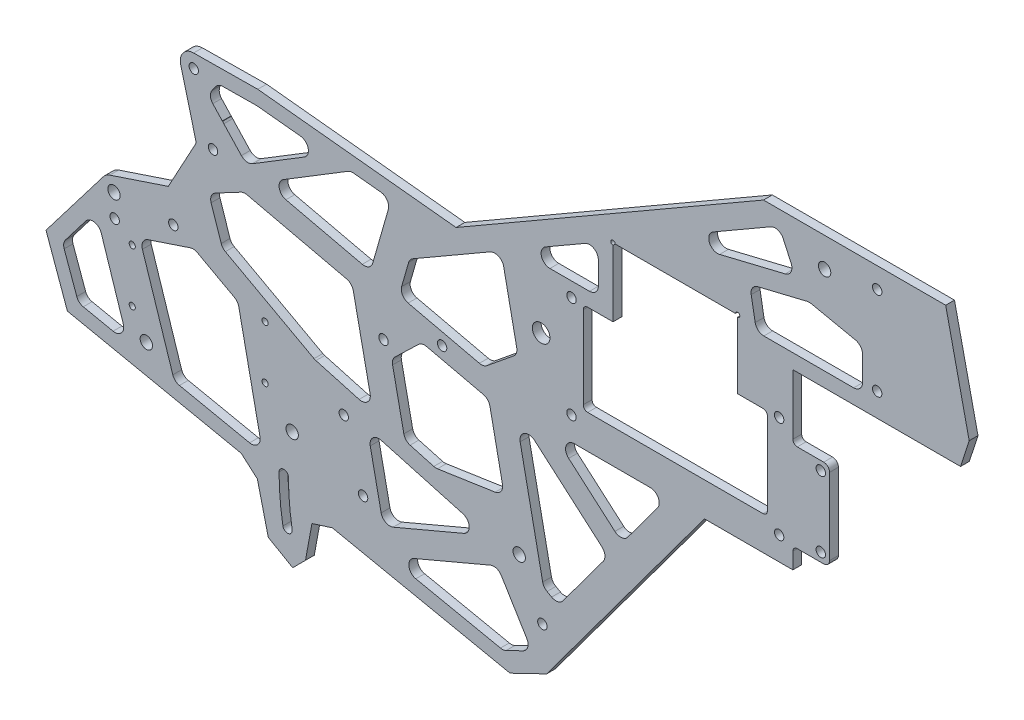
SolidWorks part; units mm, degrees
material "Thornel Mat VMA"
ref_plane "Front Plane" through (0, 0, 0) normal (0, 0, 1) x (1, 0, 0)
ref_plane "Top Plane" through (0, 0, 0) normal (0, 1, 0) x (1, 0, 0)
ref_plane "Right Plane" through (0, 0, 0) normal (1, 0, 0) x (0, 0, -1)
sketch "Sketch1" plane through (0, 0, 0) normal (0, 0, 1) x (1, 0, 0)
  line L1 (-20.4587, 47.6) -> (-183.6375, 47.6)
  line L2 (-20.4587, 47.6) -> (-20.4587, -36.0143)
  line L3 (-20.4587, -36.0143) -> (-183.6375, -36.0143)
  line L4 (-183.6375, 47.6) -> (-183.6375, -36.0143)
extrude "Boss-Extrude1" add sketch "Sketch1" along normal blind 3
sketch "Sketch2" plane through (0, 0, 3) normal (0, 0, 1) x (1, 0, 0)
  circle A0 centre (-24.2887, 24) radius 3
  dimension "D1" = 6
extrude "Cut-Extrude1" cut sketch "Sketch2" against normal blind 70
sketch "Sketch3" plane through (0, 0, 3) normal (0, 0, 1) x (1, 0, 0)
  line L4 (-20.4587, -36.0143) -> (-20.4587, 47.6)
  line L5 (-20.4587, 47.6) -> (-183.6375, 47.6)
  line L6 (-183.6375, 47.6) -> (-183.6375, -36.0143)
  line L7 (-183.6375, -36.0143) -> (-20.4587, -36.0143)
  line L8 (-20.4587, -36.0143) -> (-20.4587, 47.6)
  line L9 (-20.4587, 47.6) -> (-41.1202, 47.6)
  line L10 (-183.6375, 47.6) -> (-183.6375, -36.0143)
  line L11 (-183.6375, -36.0143) -> (-20.4587, -36.0143)
  line L13 (51.3713, 101) -> (-41.1202, 47.6)
  line L14 (-41.1202, 47.6) -> (-120.7247, 47.6)
  line L15 (-204.873, 47.6) -> (-204.873, -81.5667)
  line L16 (-204.873, -81.5667) -> (-34.873, -81.5667)
  line L17 (-34.873, -81.5667) -> (61.3713, -26)
  line L18 (61.3713, -26) -> (61.3713, 2.5)
  line L19 (62.8713, 4) -> (71.8713, 4)
  line L20 (73.8713, 6) -> (73.8713, 32)
  line L21 (71.8713, 34) -> (62.8713, 34)
  line L22 (61.3713, 35.5) -> (61.3713, 56)
  line L23 (61.3713, 56) -> (121.3713, 56)
  line L24 (121.3713, 56) -> (121.3713, 101)
  line L25 (121.3713, 101) -> (51.3713, 101)
  line L26 (51.3713, 101) -> (-41.1202, 47.6)
  line L27 (-167.8527, 47.6) -> (-120.7247, 47.6)
  line L28 (-204.873, 47.6) -> (-204.873, -81.5667)
  line L29 (-204.873, -81.5667) -> (-34.873, -81.5667)
  line L30 (-34.873, -81.5667) -> (61.3713, -26)
  line L31 (61.3713, -26) -> (61.3713, 2.5)
  line L32 (62.8713, 4) -> (71.8713, 4)
  line L33 (73.8713, 6) -> (73.8713, 32)
  line L34 (71.8713, 34) -> (62.8713, 34)
  line L35 (61.3713, 35.5) -> (61.3713, 56)
  line L36 (61.3713, 56) -> (121.3713, 56)
  line L37 (121.3713, 56) -> (121.3713, 101)
  line L38 (121.3713, 101) -> (51.3713, 101)
  line L265 (-167.8527, 47.6) -> (-204.873, 47.6)
  line L266 (-183.6375, 47.6) -> (-204.873, 47.6)
  circle A0 centre (70.8713, 31) radius 1.6 construction
  circle A1 centre (70.8713, 7) radius 1.6 construction
  arc A2 (71.8713, 4) -> (73.8713, 6) centre (71.8713, 6) ccw
  arc A3 (73.8713, 32) -> (71.8713, 34) centre (71.8713, 32) ccw
  arc A4 (71.8713, 4) -> (73.8713, 6) centre (71.8713, 6) ccw
  arc A5 (73.8713, 32) -> (71.8713, 34) centre (71.8713, 32) ccw
  circle A6 centre (70.8713, 31) radius 1.6
  circle A7 centre (70.8713, 7) radius 1.6
  arc A38 (62.8713, 4) -> (61.3713, 2.5) centre (62.8713, 2.5) ccw
  arc A39 (62.8713, 4) -> (61.3713, 2.5) centre (62.8713, 2.5) ccw
  arc A40 (61.3713, 35.5) -> (62.8713, 34) centre (62.8713, 35.5) ccw
  arc A41 (61.3713, 35.5) -> (62.8713, 34) centre (62.8713, 35.5) ccw
  arc A60 (-120.7247, 47.6) -> (-167.8527, 47.6) centre (-144.2887, 24) ccw
  arc A61 (-120.7247, 47.6) -> (-167.8527, 47.6) centre (-144.2887, 24) ccw
  dimension "D1" = 0
  dimension "D2" = 0
extrude "Boss-Extrude2" add sketch "Sketch3" against normal blind 3
sketch "Sketch4" plane through (0, 0, 3) normal (0, 0, 1) x (1, 0, 0)
  line L0 (0.1713, 62.05) -> (0.1713, 39.5) construction
  line L2 (-9.9587, 10) -> (-9.9587, 38) construction
  line L3 (-8.4587, 8.5) -> (51.2013, 8.5) construction
  line L4 (52.7013, 10) -> (52.7013, 38) construction
  line L7 (41.8213, 62.8) -> (0.9213, 62.8) construction
  line L8 (0.1713, 62.05) -> (0.1713, 39.5)
  line L9 (-8.4587, 39.5) -> (0.1713, 39.5)
  line L10 (-9.9587, 10) -> (-9.9587, 38)
  line L11 (-8.4587, 8.5) -> (51.2013, 8.5)
  line L12 (52.7013, 10) -> (52.7013, 38)
  line L13 (42.5713, 39.5) -> (51.2013, 39.5)
  line L14 (42.5713, 62.05) -> (42.5713, 39.5)
  line L15 (41.8213, 62.8) -> (0.9213, 62.8)
  arc A1 (-8.4587, 39.5) -> (-9.9587, 38) centre (-8.4587, 38) ccw construction
  arc A2 (-9.9587, 10) -> (-8.4587, 8.5) centre (-8.4587, 10) ccw construction
  arc A3 (51.2013, 8.5) -> (52.7013, 10) centre (51.2013, 10) ccw construction
  arc A4 (52.7013, 38) -> (51.2013, 39.5) centre (51.2013, 38) ccw construction
  arc A5 (42.5713, 62.05) -> (41.8213, 62.8) centre (42.5713, 62.8) ccw construction
  arc A6 (0.9213, 62.8) -> (0.1713, 62.05) centre (0.1713, 62.8) ccw
  arc A7 (-8.4587, 39.5) -> (-9.9587, 38) centre (-8.4587, 38) ccw
  arc A8 (-9.9587, 10) -> (-8.4587, 8.5) centre (-8.4587, 10) ccw
  arc A9 (51.2013, 8.5) -> (52.7013, 10) centre (51.2013, 10) ccw
  arc A10 (52.7013, 38) -> (51.2013, 39.5) centre (51.2013, 38) ccw
  arc A11 (42.5713, 62.05) -> (41.8213, 62.8) centre (42.5713, 62.8) ccw
extrude "Cut-Extrude2" cut sketch "Sketch4" against normal blind 10
sketch "Sketch6" plane through (0, 0, 0) normal (0, 0, -1) x (-1, 0, 0)
  line L0 (-121.3713, 101) -> (-51.3713, 101) construction
  line L1 (-121.3713, 56) -> (-121.3713, 101) construction
  line L2 (204.873, -81.5667) -> (34.873, -81.5667) construction
  line L3 (-61.3713, -26) -> (-61.3713, 2.5) construction
  line L4 (204.873, 47.6) -> (204.873, -81.5667) construction
  circle A2 centre (158.6381, -45.9257) radius 2.1
  circle A3 centre (169.6384, -7.2338) radius 2.1
  circle A4 centre (109.0119, -47.5134) radius 2.1
  circle A5 centre (31.7556, -45.033) radius 2.1
  circle A6 centre (-71.9717, 91) radius 2.1
  dimension "D1" = 10
  dimension "D2" = 49.3996
  dimension "D3" = 36.5337
  dimension "D4" = 93.1269
  dimension "D5" = 34.0533
  dimension "D6" = 95.8611
  dimension "D7" = 35.641
  dimension "D8" = 46.2349
  dimension "D9" = 35.2346
  dimension "D10" = 74.3329
  dimension "D11" = 4.2
extrude "Cut-Extrude3" cut sketch "Sketch6" against normal blind 10
sketch "Sketch7" plane through (0, 0, 3) normal (0, 0, 1) x (1, 0, 0)
  circle A0 centre (56.7013, 5) radius 1.6
  circle A1 centre (-13.9587, 5) radius 1.6
  circle A2 centre (56.7013, 39.6) radius 1.6
  circle A3 centre (-13.9587, 39.6) radius 1.6
  dimension "D1" = 3.2
extrude "Cut-Extrude4" cut sketch "Sketch7" against normal blind 10
sketch "Sketch8" plane through (0, 0, 0) normal (0, 0, -1) x (-1, 0, 0)
  circle A0 centre (163.4287, -37.6667) radius 1.05
  circle A1 centre (163.4287, -19.6667) radius 1.05
  circle A2 centre (118.2287, -37.6667) radius 1.05
  circle A3 centre (118.2287, -19.6667) radius 1.05
  dimension "D1" = 2.1
extrude "Cut-Extrude5" cut sketch "Sketch8" against normal blind 10
sketch "Sketch9" plane through (0, 0, 0) normal (0, 0, -1) x (-1, 0, 0)
  line L0 (-118.4267, 56) -> (-121.3713, 65.0628)
  line L1 (-61.3713, 56) -> (-121.3713, 56) construction
  line L2 (-121.3713, 65.0628) -> (-121.3713, 56)
  line L3 (-121.3713, 56) -> (-118.4267, 56)
  line L4 (-121.3713, 65.0628) -> (-113.3713, 101)
  line L5 (-113.3713, 101) -> (-121.3713, 101)
  line L6 (-121.3713, 101) -> (-121.3713, 65.0628)
  line L7 (-17.2669, -51.4637) -> (-61.3713, 0.5)
  line L8 (34.873, -81.5667) -> (-61.3713, -26) construction
  line L9 (-61.3713, 0.5) -> (-61.3713, -26)
  line L10 (-61.3713, -26) -> (-17.2669, -51.4637)
  line L11 (104.2003, -81.5667) -> (102.2857, -71.1635)
  line L12 (102.2857, -71.1635) -> (95.3446, -68.9652)
  line L13 (95.3446, -68.9652) -> (34.873, -81.5667)
  line L14 (34.873, -81.5667) -> (104.2003, -81.5667)
  line L15 (117.4045, -81.5667) -> (120.8632, -67.2922)
  line L16 (204.873, -81.5667) -> (34.873, -81.5667) construction
  line L17 (120.8632, -67.2922) -> (126.3485, -62.5044)
  line L18 (126.3485, -62.5044) -> (185.4974, -50.1785)
  line L19 (185.4974, -50.1785) -> (192.7819, -29.967)
  line L20 (192.7819, -29.967) -> (177.6384, -10.1551)
  line L21 (177.6384, -10.1551) -> (177.6384, 23.9998)
  line L22 (177.6384, 23.9998) -> (204.873, 23.9998)
  line L23 (204.873, 47.6) -> (204.873, -81.5667) construction
  line L24 (204.873, 23.9998) -> (204.873, -81.5667)
  line L25 (204.873, -81.5667) -> (117.4045, -81.5667)
  line L26 (-50.2448, 61) -> (-83.5713, 61)
  line L28 (-85.0713, 62.5) -> (-85.0713, 73.769)
  line L30 (-83.9897, 75.2094) -> (-66.2924, 80.35)
  line L32 (-65.5204, 80.3673) -> (-47.7224, 76.05)
  line L34 (-46.5996, 74.3275) -> (-48.7684, 62.2352)
  line L36 (-25.3142, 76.7885) -> (-59.5197, 85.0857)
  line L38 (-60.5306, 87.1663) -> (-56.3939, 96.2292)
  line L40 (-54.2793, 96.9054) -> (-24.2105, 79.5452)
  line L41 (9.9587, 10) -> (9.9587, 38) construction
  line L42 (-51.2013, 8.5) -> (8.4587, 8.5) construction
  arc A0 (-48.7684, 62.2352) -> (-50.2448, 61) centre (-50.2448, 62.5) cw
  arc A1 (-46.5996, 74.3275) -> (-47.7224, 76.05) centre (-48.076, 74.5923) ccw
  arc A2 (-83.5713, 61) -> (-85.0713, 62.5) centre (-83.5713, 62.5) cw
  arc A3 (-85.0713, 73.769) -> (-83.9897, 75.2094) centre (-83.5713, 73.769) cw
  arc A4 (-65.5204, 80.3673) -> (-66.2924, 80.35) centre (-65.874, 78.9096) ccw
  arc A5 (-25.3142, 76.7885) -> (-24.2105, 79.5452) centre (-24.9605, 78.2462) ccw
  arc A6 (-59.5197, 85.0857) -> (-60.5306, 87.1663) centre (-59.1661, 86.5434) cw
  arc A7 (-54.2793, 96.9054) -> (-56.3939, 96.2292) centre (-55.0293, 95.6064) ccw
  line M29 (204.873, -81.5667) -> (204.873, 47.6)
  line M34 (-51.3713, 101) -> (-121.3713, 101)
  line M35 (-121.3713, 101) -> (-121.3713, 56)
  line M36 (-121.3713, 56) -> (-61.3713, 56)
  line M45 (-61.3713, 2.5) -> (-61.3713, -26)
  line M46 (-61.3713, -26) -> (34.873, -81.5667)
  line M47 (34.873, -81.5667) -> (204.873, -81.5667)
  dimension "D1" = 1.5
  dimension "D2" = 85.3859
  dimension "D3" = 92.327
  dimension "D4" = 94.2416
  dimension "D5" = 107.4459
  dimension "D6" = 110.9045
  dimension "D7" = 116.3898
  dimension "D8" = 167.6797
  dimension "D9" = 34.1692
  dimension "D10" = 175.5387
  dimension "D11" = 182.8232
  dimension "D12" = 27.2256
  dimension "D13" = 34.9192
  dimension "D14" = 35.2728
  dimension "D15" = 56.5583
  dimension "D16" = 57.6811
  dimension "D17" = 58.0347
  dimension "D18" = 58.7271
  dimension "D19" = 64.238
  dimension "D20" = 66.3526
  dimension "D21" = 75.4791
  dimension "D22" = 76.2511
  dimension "D23" = 93.9484
  dimension "D24" = 15.4998
  dimension "D25" = 52.5
  dimension "D26" = 68.2885
  dimension "D27" = 56.5628
  dimension "D28" = 58.6785
  dimension "D29" = 75.7922
  dimension "D32" = 123.33
  dimension "D33" = 128.3853
  dimension "D47" = 8
  dimension "D48" = 18.6551
  dimension "D49" = 38.467
extrude "Cut-Extrude6" cut sketch "Sketch9" against normal blind 10 contours L22 L21 L20 L19 L18 L17 L15 M47 M29 | L12 L13 L11 M47 | L7 M46 M45 | L32 A4 L30 A3 L28 A2 L26 A0 L34 A1 | L40 A7 L38 A6 L36 A5 | L0 M36 M35 | L4 M35 M34
sketch "Sketch10" plane through (0, 0, 3) normal (0, 0, 1) x (1, 0, 0)
  line L0 (17.2669, -51.4637) -> (10.2058, -59.7831)
  line L1 (10.2058, -59.7831) -> (-34.873, -81.5667)
  line L2 (-34.873, -81.5667) -> (17.2669, -51.4637)
  line L3 (-9.9587, 38) -> (-9.9587, 10) construction
  line L4 (-8.4587, 8.5) -> (51.2013, 8.5) construction
  dimension "D1" = 20.1645
  dimension "D2" = 68.2831
extrude "Boss-Extrude3" add sketch "Sketch10" against normal blind 3
sketch "Sketch11" plane through (0, 0, 0) normal (0, 0, -1) x (-1, 0, 0)
  line L0 (182.0256, -45.065) -> (186.8761, -31.6065)
  line L1 (204.873, 47.6) -> (204.873, 23.9998) construction
  line L2 (186.6567, -30.187) -> (177.4937, -18.1993)
  line L3 (-113.3713, 101) -> (-51.3713, 101) construction
  line L4 (174.8756, -18.6461) -> (165.68, -46.9072)
  line L6 (167.4124, -48.8398) -> (180.9204, -46.0249)
  arc A0 (112.1618, -76.8394) -> (109.0086, -76.294) centre (110.5852, -76.5667) cw
  arc A1 (112.1618, -76.8394) -> (113.473, -61.5667) centre (23.873, -61.5667) ccw
  arc A2 (110.273, -61.5667) -> (109.0086, -76.294) centre (23.873, -61.5667) cw
  arc A3 (113.473, -61.5667) -> (110.273, -61.5667) centre (111.873, -61.5667) ccw
  circle A4 centre (23.873, -61.5667) radius 1.6
  arc A5 (180.9204, -46.0249) -> (182.0256, -45.065) centre (180.6144, -44.5564) ccw
  arc A6 (186.8761, -31.6065) -> (186.6567, -30.187) centre (185.465, -31.0979) ccw
  arc A7 (177.4937, -18.1993) -> (174.8756, -18.6461) centre (176.302, -19.1102) ccw
  arc A8 (167.4124, -48.8398) -> (165.68, -46.9072) centre (167.1064, -47.3713) cw
  dimension "D1" = 1.6
  dimension "D2" = 89.6
  dimension "D3" = 17.9969
  dimension "D4" = 1.5
  dimension "D5" = 18.2163
  dimension "D6" = 19.408
  dimension "D7" = 22.8475
  dimension "D8" = 23.9526
  dimension "D9" = 27.3793
  dimension "D10" = 29.9974
  dimension "D11" = 92.7112
  dimension "D12" = 93
  dimension "D13" = 119.1993
  dimension "D14" = 162.5667
extrude "Cut-Extrude7" cut sketch "Sketch11" against normal blind 3
sketch "Sketch12" plane through (0, 0, 0) normal (0, 0, -1) x (-1, 0, 0)
  line L0 (204.873, 47.6) -> (204.873, 23.9998) construction
  line L1 (-113.3713, 101) -> (-51.3713, 101) construction
  circle A0 centre (-90.0713, 94) radius 1.6
  circle A1 centre (-90.0713, 64) radius 1.6
  dimension "D1" = 3.2
  dimension "D2" = 294.9443
  dimension "D3" = 7
  dimension "D4" = 37
extrude "Cut-Extrude8" cut sketch "Sketch12" against normal blind 3
sketch "Sketch15" plane through (0, 0, 3) normal (0, 0, 1) x (1, 0, 0)
  line L0 (-104.2003, -81.5667) -> (-117.4045, -81.5667)
  line L1 (-117.4045, -81.5667) -> (-117.1382, -82.6658)
  line L2 (-117.1382, -82.6658) -> (-108.8293, -87.4629)
  line L3 (-108.8293, -87.4629) -> (-104.4861, -83.1198)
  line L4 (-104.4861, -83.1198) -> (-104.2003, -81.5667)
  line L5 (52.7013, 10) -> (52.7013, 38) construction
  line L6 (41.8213, 62.8) -> (0.9213, 62.8) construction
  dimension "D1" = 157.1875
  dimension "D2" = 161.5306
  dimension "D3" = 169.8396
  dimension "D4" = 145.4658
  dimension "D5" = 145.9198
  dimension "D6" = 150.2629
extrude "Boss-Extrude4" add sketch "Sketch15" against normal blind 3
sketch "Sketch16" plane through (0, 0, 0) normal (0, 0, -1) x (-1, 0, 0)
  line L0 (11.2698, -56.8332) -> (-11.3083, -45.9227)
  line L1 (0.4601, -6.3291) -> (-30.5111, -21.7344)
  line L2 (-11.7993, -45.5427) -> (-23.6576, -31.5713)
  line L3 (204.873, 47.6) -> (204.873, 23.9998) construction
  line L4 (-23.182, -29.2577) -> (27.4491, -4.0733)
  line L5 (-32.3227, -21.3621) -> (-41.0149, -11.1209)
  line L6 (29.5868, -5.7168) -> (22.3602, -41.0637)
  line L7 (-61.3713, 56) -> (-118.4267, 56) construction
  line L8 (22.1716, -41.5438) -> (13.2034, -56.2631)
  line L9 (-41.3713, -10.1503) -> (-41.3713, -1)
  line L11 (-39.8713, 0.5) -> (-2.7749, 0.5)
  line L13 (-1.5138, -0.1879) -> (1.0532, -4.174)
  arc A0 (13.2034, -56.2631) -> (11.2698, -56.8332) centre (11.9225, -55.4826) cw
  arc A1 (22.1716, -41.5438) -> (22.3602, -41.0637) centre (20.8906, -40.7633) ccw
  arc A2 (29.5868, -5.7168) -> (27.4491, -4.0733) centre (28.1172, -5.4164) ccw
  arc A3 (-11.3083, -45.9227) -> (-11.7993, -45.5427) centre (-10.6557, -44.5721) cw
  arc A4 (-23.6576, -31.5713) -> (-23.182, -29.2577) centre (-22.514, -30.6007) cw
  arc A5 (0.4601, -6.3291) -> (1.0532, -4.174) centre (-0.208, -4.9861) ccw
  arc A6 (-1.5138, -0.1879) -> (-2.7749, 0.5) centre (-2.7749, -1) ccw
  arc A7 (-30.5111, -21.7344) -> (-32.3227, -21.3621) centre (-31.1791, -20.3914) cw
  arc A8 (-41.0149, -11.1209) -> (-41.3713, -10.1503) centre (-39.8713, -10.1503) cw
  arc A9 (-41.3713, -1) -> (-39.8713, 0.5) centre (-39.8713, -1) cw
  dimension "D1" = 1.5
  dimension "D2" = 175.2862
  dimension "D3" = 176.7558
  dimension "D4" = 177.4239
  dimension "D5" = 182.5128
  dimension "D6" = 182.7014
  dimension "D7" = 191.6696
  dimension "D8" = 193.6032
  dimension "D9" = 203.8199
  dimension "D10" = 204.413
  dimension "D11" = 205.081
  dimension "D12" = 206.3868
  dimension "D13" = 215.5287
  dimension "D14" = 216.6723
  dimension "D15" = 235.3841
  dimension "D16" = 245.888
  dimension "D17" = 55.5
extrude "Cut-Extrude11" cut sketch "Sketch16" against normal blind 3
sketch "Sketch18" plane through (0, 0, 0) normal (0, 0, -1) x (-1, 0, 0)
  line L0 (7.0787, 61.4804) -> (31.6415, 47.299)
  line L1 (-52.7013, 38) -> (-52.7013, 10) construction
  line L2 (30.8915, 44.5) -> (6.3287, 44.5)
  line L3 (-0.9213, 62.8) -> (-41.8213, 62.8) construction
  line L4 (4.8287, 46) -> (4.8287, 60.1813)
  arc A0 (4.8287, 60.1813) -> (7.0787, 61.4804) centre (6.3287, 60.1813) cw
  arc A1 (4.8287, 46) -> (6.3287, 44.5) centre (6.3287, 46) ccw
  arc A2 (31.6415, 47.299) -> (30.8915, 44.5) centre (30.8915, 46) cw
  dimension "D1" = 1.5
  dimension "D2" = 57.53
  dimension "D3" = 59.78
  dimension "D4" = 83.5928
  dimension "D5" = 1.3196
extrude "Cut-Extrude13" cut sketch "Sketch18" against normal blind 3
sketch "Sketch19" plane through (0, 0, 3) normal (0, 0, 1) x (1, 0, 0)
  line L0 (52.7013, 10) -> (52.7013, 38) construction
  line L1 (41.8213, 62.8) -> (0.9213, 62.8) construction
  circle A0 centre (-91.4566, -33.7689) radius 1.6
  circle A1 centre (-77.9328, -4.7671) radius 1.6
  circle A2 centre (-149.4603, -6.7213) radius 1.6
  circle A3 centre (-135.9365, 22.2805) radius 1.6
  dimension "D1" = 3.2
  dimension "D2" = 130.6341
  dimension "D3" = 144.1579
  dimension "D4" = 188.6378
  dimension "D5" = 202.1616
  dimension "D6" = 40.5195
  dimension "D7" = 67.5671
  dimension "D8" = 69.5213
  dimension "D9" = 96.5689
extrude "Cut-Extrude14" cut sketch "Sketch19" against normal blind 3
sketch "Sketch20" plane through (0, 0, 3) normal (0, 0, 1) x (1, 0, 0)
  line L0 (-87.4344, -49.9884) -> (-62.9225, 2.5774) construction
  line L1 (-87.4344, -49.9884) -> (-164.4705, -14.0659) construction
  line L2 (-62.9225, 2.5774) -> (-139.9587, 38.5) construction
  line L3 (-164.4705, -14.0659) -> (-139.9587, 38.5) construction
  line L6 (-87.4344, -49.9884) -> (-139.9587, 38.5) construction
  line L7 (-62.9225, 2.5774) -> (-164.4705, -14.0659) construction
  line L8 (52.7013, 10) -> (52.7013, 38) construction
  line L9 (41.8213, 62.8) -> (0.9213, 62.8) construction
  circle A0 centre (-84.8823, -54.288) radius 1.6
  circle A1 centre (-169.4047, -14.8745) radius 1.6
  circle A2 centre (-57.9884, 3.3861) radius 1.6
  circle A3 centre (-142.5108, 42.7996) radius 1.6
  dimension "D1" = 3.2
  dimension "D2" = 5
  dimension "D3" = 5
  dimension "D4" = 5
  dimension "D5" = 5
  dimension "D6" = 110.6897
  dimension "D7" = 137.5836
  dimension "D8" = 195.2122
  dimension "D9" = 222.1061
  dimension "D10" = 20.0004
extrude "Cut-Extrude15" cut sketch "Sketch20" against normal blind 3
sketch "Sketch22" plane through (0, 0, 3) normal (0, 0, 1) x (1, 0, 0)
  line L0 (-37.1234, -75.9903) -> (-76.3231, -67.8216)
  line L1 (-37.1234, -75.9903) -> (-27.4515, -71.3165)
  line L2 (-27.4515, -71.3165) -> (-39.179, -52.0683)
  line L3 (-42.6859, -44.8659) -> (-83.4484, -33.5518)
  line L4 (-83.4484, -33.5518) -> (-77.9834, -59.8361)
  line L5 (-119.0289, -58.9223) -> (-149.0861, -52.6587)
  line L6 (-149.0861, -52.6587) -> (-160.8985, -16.3554)
  line L7 (-160.8985, -16.3554) -> (-142.4426, -10.2002)
  line L8 (-142.4426, -10.2002) -> (-127.4625, -18.3601)
  line L9 (-127.4625, -18.3601) -> (-119.0289, -58.9223)
  line L10 (-60.2062, -33.7761) -> (-36.8146, -30.2729)
  line L11 (-36.8146, -30.2729) -> (-42.1035, -4.4033)
  line L12 (-42.1035, -4.4033) -> (-64.8597, 0.8733)
  line L13 (-64.8597, 0.8733) -> (-75.1752, -9.0737)
  line L14 (-75.1752, -9.0737) -> (-70.6413, -30.8797)
  line L15 (-70.6413, -30.8797) -> (-60.2062, -33.7761)
  line L16 (-81.4807, -27.8711) -> (-88.6019, 6.3786)
  line L17 (-88.6019, 6.3786) -> (-125.4554, 14.9242)
  line L18 (-125.4554, 14.9242) -> (-137.3952, 8.5985)
  line L19 (-137.3952, 8.5985) -> (-132.7901, -5.2095)
  line L20 (-132.7901, -5.2095) -> (-101.2724, -22.3777)
  line L21 (-101.2724, -22.3777) -> (-81.4807, -27.8711)
  line L22 (-43.8661, 4.2176) -> (-32.2369, 13.699)
  line L23 (-32.2369, 13.699) -> (-37.5323, 39.6)
  line L24 (-37.5323, 39.6) -> (-64.3985, 39.6)
  line L25 (-64.3985, 39.6) -> (-72.6338, 10.8882)
  line L26 (-72.6338, 10.8882) -> (-43.8661, 4.2176)
  line L28 (-82.3882, 13.1501) -> (-74.8017, 39.6)
  line L29 (-74.8017, 39.6) -> (-129.552, 39.6)
  line L30 (-129.552, 39.6) -> (-133.929, 33.4456)
  line L31 (-133.929, 33.4456) -> (-124.0034, 22.7997)
  line L32 (-124.0034, 22.7997) -> (-82.3882, 13.1501)
  line L33 (-171.088, -2.8873) -> (-151.1667, 3.7566)
  line L34 (-151.1667, 3.7566) -> (-141.6423, 21.3231)
  line L35 (-141.6423, 21.3231) -> (-146.9443, 41.6428)
  line L36 (-167.4124, -48.8398) -> (-180.9204, -46.0249) construction
  line L37 (-173.2787, -4.4514) -> (-177.6384, -10.1551)
  line L38 (-34.873, -81.5667) -> (10.2058, -59.7831) construction
  line L39 (-13.2034, -56.2631) -> (-22.1716, -41.5438) construction
  line L40 (-39.179, -52.0683) -> (-76.3231, -67.8216)
  line L41 (-42.6859, -44.8659) -> (-77.9834, -59.8361)
  line L42 (-142.5567, 47.3813) -> (-120.7247, 47.6)
  line L43 (-192.7819, -29.967) -> (-177.6384, -10.1551) construction
  line L44 (-142.5108, 42.7996) -> (-169.6384, -7.2338) construction
  line L45 (-22.3602, -41.0637) -> (-29.5868, -5.7168) construction
  line L46 (-41.1202, 47.6) -> (-120.7247, 47.6) construction
  line L47 (-174.8756, -18.6461) -> (-165.68, -46.9072) construction
  line L48 (-120.7247, 47.6) -> (-129.552, 69.989)
  line L49 (-129.552, 69.989) -> (-217.9731, 55.7464)
  line L50 (-217.9731, 55.7464) -> (-212.0666, -12.7046)
  line L51 (-212.0666, -12.7046) -> (-177.6384, -10.1551)
  circle A0 centre (-169.6384, -7.2338) radius 4.5819
  circle A1 centre (-142.5108, 42.7996) radius 4.5819
  circle A2 centre (-57.9884, 3.3861) radius 1.6 construction
  point P63 (-65.4238, -32.3279)
  dimension "D16" = 4
  dimension "D1" = 11
  dimension "D2" = 8
  dimension "D3" = 6
  dimension "D4" = 20
  dimension "D5" = 6
  dimension "D6" = 12
  dimension "D7" = 8
  dimension "D8" = 8
  dimension "D9" = 10
  dimension "D10" = 10
  dimension "D11" = 21
  dimension "D12" = 14
  dimension "D13" = 40
  dimension "D14" = 9
  dimension "D15" = 16
extrude "Cut-Extrude16" cut sketch "Sketch22" against normal blind 10 contours L2 L40 L0 L1 | L41 L3 L4 | L14 L15 L10 L11 L12 L13 | L25 L26 L22 L23 L24 | L20 L21 L16 L17 L18 L19 | L9 L8 L7 L6 L5 | L31 L32 L28 L29 L30 | L44 L35 A1 L42 L48 L49 L50 L51 L37 A0 L33 | L35 L44 L33 L34
fillet "Fillet2" radius 3 34 edges at (-37.5323, 39.6, 1.5) (-64.3985, 39.6, 1.5) (-32.2369, 13.699, 1.5) (-43.8661, 4.2176, 1.5) (-82.3882, 13.1501, 1.5) (-72.6338, 10.8882, 1.5) (-124.0034, 22.7997, 1.5) (-132.7901, -5.2095, 1.5) (-101.2724, -22.3777, 1.5) (-81.4807, -27.8711, 1.5) (-133.929, 33.4456, 1.5) (-129.552, 39.6, 1.5) (-137.3952, 8.5985, 1.5) (-160.8985, -16.3554, 1.5) (-88.6019, 6.3786, 1.5) (-74.8017, 39.6, 1.5) (-125.4554, 14.9242, 1.5) (-142.4426, -10.2002, 1.5) (-127.4625, -18.3601, 1.5) (-119.0289, -58.9223, 1.5) (-149.0861, -52.6587, 1.5) (-70.6413, -30.8797, 1.5) (-60.2062, -33.7761, 1.5) (-42.1035, -4.4033, 1.5) (-36.8146, -30.2729, 1.5) (-64.8597, 0.8733, 1.5) (-75.1752, -9.0737, 1.5) (-83.4484, -33.5518, 1.5) (-77.9834, -59.8361, 1.5) (-76.3231, -67.8216, 1.5) (-39.179, -52.0683, 1.5) (-42.6859, -44.8659, 1.5) (-37.1234, -75.9903, 1.5) (-27.4515, -71.3165, 1.5)
sketch "Sketch23" plane through (0, 0, 3) normal (0, 0, 1) x (1, 0, 0)
  line L0 (-15.1302, -62.3797) -> (12.2183, -50.6967)
  line L1 (12.2183, -50.6967) -> (46.1657, -12.476)
  line L2 (46.1657, -12.476) -> (46.1657, 2.4504)
  line L3 (46.1657, 2.4504) -> (-9.1293, 2.4504)
  line L4 (-9.1293, 2.4504) -> (-16.2227, -2.8307)
  line L5 (-16.2227, -2.8307) -> (-26.155, 1.2793)
  line L6 (-26.155, 1.2793) -> (-39.1064, -4.2534)
  line L7 (-39.1064, -4.2534) -> (-15.1302, -62.3797)
  line L8 (85.0713, 62.5) -> (85.0713, 73.769) construction
  line L9 (113.3713, 101) -> (51.3713, 101) construction
  line L10 (61.3713, 0.5) -> (52.8467, -9.5437)
  line L11 (17.2669, -51.4637) -> (61.3713, 0.5) construction
  line L12 (52.8467, -9.5437) -> (61.3713, -9.5437)
  line L13 (61.3713, -9.5437) -> (61.3713, 0.5)
  dimension "D1" = 38.9056
  dimension "D2" = 72.853
  dimension "D3" = 94.2006
  dimension "D4" = 100.2015
  dimension "D5" = 101.294
  dimension "D6" = 111.2263
  dimension "D7" = 124.1778
  dimension "D8" = 98.5496
  dimension "D9" = 99.7207
  dimension "D10" = 103.8307
  dimension "D11" = 105.2534
  dimension "D12" = 113.476
  dimension "D13" = 151.6967
extrude "Boss-Extrude5" add sketch "Sketch23" against normal blind 3
sketch "Sketch24" plane through (0, 0, 3) normal (0, 0, 1) x (1, 0, 0)
  line L0 (61.3713, -3) -> (31.2918, -3)
  line L1 (31.2918, -3) -> (-22.4178, -75.5479)
  line L2 (-22.4178, -75.5479) -> (68.0776, -67.6539)
  line L3 (68.0776, -67.6539) -> (61.3713, -3)
  line L4 (-17.6291, -52.2733) -> (-2.3415, -31.6237)
  line L5 (2.0346, -22.9964) -> (-17.9678, -5.6327)
  line L6 (-2.5637, -29.5984) -> (-29.8659, -5.898)
  line L7 (85.0713, 62.5) -> (85.0713, 73.769) construction
  line L8 (-32.3188, -7.3312) -> (-23.6278, -49.8413)
  line L9 (-16.9844, -3) -> (15.8728, -3)
  line L10 (-22.8847, -50.8531) -> (-19.5612, -52.6931)
  line L11 (113.3713, 101) -> (51.3713, 101) construction
  line L12 (17.0783, -5.3925) -> (4.2235, -22.7562)
  arc A0 (-19.5612, -52.6931) -> (-17.6291, -52.2733) centre (-18.8346, -51.3808) ccw
  arc A1 (-22.8847, -50.8531) -> (-23.6278, -49.8413) centre (-22.1582, -49.5408) cw
  arc A2 (-32.3188, -7.3312) -> (-29.8659, -5.898) centre (-30.8492, -7.0307) cw
  arc A3 (-2.3415, -31.6237) -> (-2.5637, -29.5984) centre (-3.547, -30.7312) ccw
  arc A4 (2.0346, -22.9964) -> (4.2235, -22.7562) centre (3.0089, -21.7818) ccw
  arc A5 (-17.9678, -5.6327) -> (-16.9844, -3) centre (-16.9844, -4.5) cw
  arc A6 (15.8728, -3) -> (17.0783, -5.3925) centre (15.8728, -4.5) cw
  dimension "D1" = 1.5
  dimension "D2" = 1.5571
  dimension "D3" = 16.9937
  dimension "D4" = 23.7
  dimension "D5" = 53.7795
  dimension "D6" = 67.993
  dimension "D7" = 69.1986
  dimension "D8" = 80.8479
  dimension "D9" = 82.0624
  dimension "D10" = 83.0367
  dimension "D11" = 87.4128
  dimension "D12" = 87.6351
  dimension "D13" = 102.0558
  dimension "D14" = 102.7004
  dimension "D15" = 104.6325
  dimension "D16" = 107.2295
  dimension "D17" = 108.6991
  dimension "D18" = 104
  dimension "D20" = 107.4891
  dimension "D38" = 168.6539
  dimension "D39" = 176.5479
extrude "Cut-Extrude17" cut sketch "Sketch24" against normal blind 3
sketch "Sketch25" plane through (0, 0, 3) normal (0, 0, 1) x (1, 0, 0)
  line L0 (87.5622, 58.5714) -> (87.5622, 78.331)
  line L1 (87.5622, 78.331) -> (64.471, 87.209)
  line L2 (64.471, 87.209) -> (55.9377, 98.9782)
  line L3 (55.9377, 98.9782) -> (45.5782, 95.3423)
  line L4 (45.5782, 95.3423) -> (17.6787, 75.1139)
  line L5 (17.6787, 75.1139) -> (44.9652, 66.8338)
  line L6 (44.9652, 66.8338) -> (48.6841, 56.2378)
  line L7 (48.6841, 56.2378) -> (87.5622, 58.5714)
  line L8 (85.0713, 62.5) -> (85.0713, 73.769) construction
  line L9 (113.3713, 101) -> (51.3713, 101) construction
  dimension "D1" = 2.4909
  dimension "D2" = 20.6003
  dimension "D3" = 29.1336
  dimension "D4" = 36.3872
  dimension "D5" = 39.4932
  dimension "D6" = 40.1061
  dimension "D7" = 67.3926
  dimension "D8" = 2.0218
  dimension "D9" = 5.6577
  dimension "D10" = 13.791
  dimension "D11" = 22.669
  dimension "D12" = 34.1662
  dimension "D14" = 42.4286
extrude "Boss-Extrude6" add sketch "Sketch25" against normal blind 3
sketch "Sketch26" plane through (0, 0, 3) normal (0, 0, 1) x (1, 0, 0)
  line L0 (26.3142, 75.0564) -> (60.5197, 83.3537)
  line L2 (61.5306, 85.4342) -> (57.3939, 94.4972)
  line L4 (55.2793, 95.1734) -> (25.2105, 77.8132)
  line L6 (50.2448, 61) -> (83.5713, 61)
  line L7 (73.8713, 6) -> (73.8713, 32) construction
  line L8 (85.0713, 62.5) -> (85.0713, 73.6788)
  line L9 (113.3713, 101) -> (51.3713, 101) construction
  line L10 (83.8812, 75.1465) -> (67.2415, 78.6592)
  line L12 (66.5781, 78.6493) -> (48.0618, 74.1577)
  line L14 (46.939, 72.4352) -> (48.7684, 62.2352)
  arc A0 (50.2448, 61) -> (48.7684, 62.2352) centre (50.2448, 62.5) cw
  arc A1 (83.5713, 61) -> (85.0713, 62.5) centre (83.5713, 62.5) ccw
  arc A2 (85.0713, 73.6788) -> (83.8812, 75.1465) centre (83.5713, 73.6788) ccw
  arc A3 (46.939, 72.4352) -> (48.0618, 74.1577) centre (48.4154, 72.7) cw
  arc A4 (66.5781, 78.6493) -> (67.2415, 78.6592) centre (66.9317, 77.1915) cw
  arc A5 (60.5197, 83.3537) -> (61.5306, 85.4342) centre (60.1661, 84.8114) ccw
  arc A6 (26.3142, 75.0564) -> (25.2105, 77.8132) centre (25.9605, 76.5141) cw
  arc A7 (55.2793, 95.1734) -> (57.3939, 94.4972) centre (56.0293, 93.8743) cw
  dimension "D1" = 1.5
  dimension "D2" = 10.0098
  dimension "D3" = 11.2
  dimension "D4" = 6.6298
  dimension "D5" = 7.2932
  dimension "D6" = 12.3407
  dimension "D7" = 13.3517
  dimension "D8" = 13.7053
  dimension "D9" = 16.4774
  dimension "D10" = 18.592
  dimension "D11" = 23.6265
  dimension "D12" = 25.103
  dimension "D13" = 25.4559
  dimension "D14" = 5.8266
  dimension "D15" = 22.3408
extrude "Cut-Extrude18" cut sketch "Sketch26" against normal blind 3
sketch "Sketch27" plane through (0, 0, 3) normal (0, 0, 1) x (1, 0, 0)
  line L1 (66.9244, 95.7692) -> (76.5752, 95.7692)
  line L2 (66.9244, 95.7692) -> (66.9244, 87.935)
  line L3 (66.9244, 87.935) -> (76.5752, 87.935)
  line L4 (76.5752, 95.7692) -> (76.5752, 87.935)
extrude "Boss-Extrude7" add sketch "Sketch27" against normal blind 3
sketch "Sketch28" plane through (0, 0, 3) normal (0, 0, 1) x (1, 0, 0)
  circle A0 centre (72.1811, 91) radius 2.1
extrude "Cut-Extrude19" cut sketch "Sketch28" against normal blind 3
sketch "Sketch29" plane through (0, 0, 3) normal (0, 0, 1) x (1, 0, 0)
  line L0 (-7.0787, 59.171) -> (-27.6415, 47.299)
  line L1 (-4.8287, 60.1813) -> (-4.8287, 46) construction
  line L2 (-6.3287, 44.5) -> (-30.8915, 44.5) construction
  line L3 (-31.6415, 47.299) -> (-7.0787, 61.4804) construction
  line L4 (-4.8287, 60.1813) -> (-4.8287, 57.8719)
  line L5 (-31.6415, 47.299) -> (-7.0787, 61.4804)
  line L6 (-26.8915, 44.5) -> (-30.8915, 44.5)
  arc A0 (-7.0787, 59.171) -> (-4.8287, 57.8719) centre (-6.3287, 57.8719) cw
  arc A1 (-27.6415, 47.299) -> (-26.8915, 44.5) centre (-26.8915, 46) ccw
  arc A2 (-31.6415, 47.299) -> (-30.8915, 44.5) centre (-30.8915, 46) ccw construction
  arc A3 (-4.8287, 60.1813) -> (-7.0787, 61.4804) centre (-6.3287, 60.1813) ccw construction
  arc A4 (-4.8287, 60.1813) -> (-7.0787, 61.4804) centre (-6.3287, 60.1813) ccw
  arc A5 (-31.6415, 47.299) -> (-30.8915, 44.5) centre (-30.8915, 46) ccw
extrude "Boss-Extrude8" add sketch "Sketch29" against normal blind 3
sketch "Sketch30" plane through (0, 0, 0) normal (0, 0, -1) x (-1, 0, 0)
  line L0 (41.1202, 47.6) -> (120.7247, 47.6)
  line L1 (41.1202, 47.6) -> (120.7247, 47.6) construction
  line L2 (120.7247, 47.6) -> (53.2445, 40.6)
  line L3 (53.2445, 40.6) -> (41.1202, 47.6)
  line L4 (-51.3713, 101) -> (41.1202, 47.6) construction
  dimension "D1" = 7
extrude "Cut-Extrude20" cut sketch "Sketch30" against normal blind 3
sketch "Sketch31" plane through (0, 0, 3) normal (0, 0, 1) x (1, 0, 0)
  line L1 (51.3713, 101) -> (-53.2445, 40.6) construction
  line L2 (-53.2445, 40.6) -> (-63.5378, 41.6678)
  line L3 (-53.2445, 40.6) -> (-120.7247, 47.6) construction
  line L4 (-41.6727, 39.1981) -> (-67.9973, 23.9996)
  line L5 (-39.981, 39.6) -> (-62.138, 39.6) construction
  line L6 (-65.0218, 37.4271) -> (-71.7629, 13.9243) construction
  line L7 (-27.6415, 47.299) -> (-7.0787, 59.171) construction
  line L8 (-79.9819, 34.3253) -> (-127.8995, 39.296)
  line L9 (-130.449, 38.3387) -> (-132.5106, 35.44) construction
  line L10 (-40.1727, 39.6) -> (-32.7008, 39.6)
  line L11 (-69.3811, 22.2286) -> (-71.4148, 15.1381)
  line L12 (-32.7008, 39.6) -> (-43.539, 46.2035)
  line L13 (-43.539, 46.2035) -> (-53.2445, 40.6)
  line L14 (-71.4148, 15.1381) -> (-81.5174, 16.1861)
  line L15 (-81.6026, 15.8891) -> (-75.8994, 35.7729) construction
  line L16 (-81.5174, 16.1861) -> (-77.4078, 30.5142)
  line L17 (-63.5378, 41.6678) -> (-125.9271, 45.6334)
  line L18 (-125.9271, 45.6334) -> (-133.0382, 39.987)
  line L19 (-133.0382, 39.987) -> (-132.4874, 35.4726)
  line L20 (-132.4874, 35.4726) -> (-130.6538, 38.0507)
  line L21 (-53.2445, 40.6) -> (-120.7247, 47.6) construction
  arc A0 (-41.6727, 39.1981) -> (-40.1727, 39.6) centre (-40.1727, 36.6) cw
  arc A1 (-67.9973, 23.9996) -> (-69.3811, 22.2286) centre (-66.4973, 21.4015) ccw
  arc A2 (-77.4078, 30.5142) -> (-79.9819, 34.3253) centre (-80.2915, 31.3413) ccw
  arc A3 (-127.8995, 39.296) -> (-130.6538, 38.0507) centre (-128.2091, 36.312) ccw
  point P24 (-40.9766, 39.6)
  point P28 (-69.0469, 23.3936)
  point P35 (-76.4206, 33.9559)
  point P41 (-129.6398, 39.4765)
  dimension "D1" = 3
  dimension "D2" = 3
  dimension "D3" = 3
  dimension "D4" = 3
  dimension "D5" = 9
extrude "Boss-Extrude9" add sketch "Sketch31" against normal blind 3
sketch "Sketch32" plane through (0, 0, 3) normal (0, 0, 1) x (1, 0, 0)
  line L0 (-77.4078, 30.5142) -> (-76.2876, 34.4194)
  line L1 (-78.8618, 38.2306) -> (-120.789, 42.5798)
  line L2 (-121.1286, 42.5957) -> (-132.6302, 42.4805)
  line L3 (-135.0449, 41.2193) -> (-136.2799, 39.4829)
  line L4 (-136.0294, 35.6983) -> (-132.7826, 32.216)
  line L5 (-132.2601, 31.6555) -> (-124.6279, 23.4696) construction
  line L6 (-81.6026, 15.8891) -> (-77.4078, 30.5142) construction
  line L7 (-53.2445, 40.6) -> (-120.7247, 47.6) construction
  line L8 (-142.5567, 47.3813) -> (-120.7247, 47.6) construction
  line L9 (-130.6538, 38.0507) -> (-132.5106, 35.44) construction
  line L10 (-77.4078, 30.5142) -> (-132.7826, 32.216)
  circle A0 centre (-142.5108, 42.7996) radius 1.6 construction
  arc A1 (-136.2799, 39.4829) -> (-136.0294, 35.6983) centre (-133.8351, 37.7441) ccw
  arc A2 (-120.789, 42.5798) -> (-121.1286, 42.5957) centre (-121.0985, 39.5959) ccw
  arc A3 (-132.6302, 42.4805) -> (-135.0449, 41.2193) centre (-132.6002, 39.4806) ccw
  arc A4 (-76.2876, 34.4194) -> (-78.8618, 38.2306) centre (-79.1714, 35.2466) ccw
  dimension "D4" = 3
  dimension "D1" = 5
  dimension "D2" = 5
  dimension "D3" = 7
extrude "Cut-Extrude21" cut sketch "Sketch32" against normal blind 10
sketch "Sketch33" plane through (0, 0, 3) normal (0, 0, 1) x (1, 0, 0)
  line L0 (-118.3005, 21.4774) -> (-89.1501, 39.2978)
  line L5 (-123.1113, 22.5929) -> (-85.164, 13.7937) construction
  line L7 (-78.8618, 38.2306) -> (-120.789, 42.5798) construction
  line L9 (-97.3456, 40.148) -> (-124.6279, 23.4696)
  line L10 (-132.2601, 31.6555) -> (-124.6279, 23.4696) construction
  line L11 (-124.6279, 23.4696) -> (-125.9216, 20.3369)
  line L12 (-125.9216, 20.3369) -> (-118.3005, 21.4774)
  line L13 (-89.1501, 39.2978) -> (-97.3456, 40.148)
  point P10 (-124.3157, 23.1346)
  point P12 (-118.3005, 21.4774)
  dimension "D1" = 5
extrude "Boss-Extrude10" add sketch "Sketch33" against normal blind 3
fillet "Fillet3" radius 3 4 edges at (-118.3005, 21.4774, 1.5) (-124.6279, 23.4696, 1.5) (-97.3456, 40.148, 1.5) (-89.1501, 39.2978, 1.5)
sketch "Sketch34" plane through (0, 0, 3) normal (0, 0, 1) x (1, 0, 0)
  line L0 (50.2448, 61) -> (83.5713, 61) construction
  line L1 (85.0713, 62.5) -> (85.0713, 73.6788) construction
  line L2 (83.5713, 61) -> (82.0713, 61)
  line L3 (85.0713, 62.5) -> (85.0713, 64)
  line L4 (83.8812, 75.1465) -> (67.2415, 78.6592) construction
  line L5 (85.0713, 72.4624) -> (85.0713, 73.6788)
  line L6 (83.8812, 75.1465) -> (82.691, 75.3978)
  line L7 (66.5781, 78.6493) -> (48.0618, 74.1577) construction
  line L8 (67.5744, 78.5889) -> (67.2415, 78.6592)
  line L9 (66.5781, 78.6493) -> (66.2475, 78.5691)
  line L10 (46.939, 72.4352) -> (48.7684, 62.2352) construction
  line L11 (51.4997, 61) -> (50.2448, 61)
  line L12 (48.7684, 62.2352) -> (48.5468, 63.4704)
  line L13 (47.1882, 71.0455) -> (46.939, 72.4352)
  line L14 (49.4339, 74.4906) -> (48.0618, 74.1577)
  line L15 (26.3142, 75.0564) -> (60.5197, 83.3537) construction
  line L16 (61.5306, 85.4342) -> (57.3939, 94.4972) construction
  line L17 (60.5197, 83.3537) -> (58.7545, 82.9255)
  line L18 (61.5306, 85.4342) -> (60.7764, 87.0866)
  line L19 (55.2793, 95.1734) -> (25.2105, 77.8132) construction
  line L20 (58.0792, 92.9958) -> (57.3939, 94.4972)
  line L21 (55.2793, 95.1734) -> (53.8501, 94.3482)
  line L22 (36.452, 77.5155) -> (26.3142, 75.0564)
  line L23 (25.2105, 77.8132) -> (34.2448, 83.0291)
  line L24 (-4.8287, 57.8719) -> (-4.8287, 46) construction
  line L25 (-6.3287, 44.5) -> (-26.8915, 44.5) construction
  line L26 (-27.6415, 47.299) -> (-7.0787, 59.171) construction
  line L27 (-6.3287, 44.5) -> (-7.8287, 44.5)
  line L28 (-4.8287, 46) -> (-4.8287, 47.5)
  line L29 (-4.8287, 55.2739) -> (-4.8287, 57.8719)
  line L30 (-7.0787, 59.171) -> (-9.3287, 57.8719)
  line L31 (-22.7934, 50.0981) -> (-27.6415, 47.299)
  line L32 (-26.8915, 44.5) -> (-21.2934, 44.5)
  line L33 (4.2235, -22.7562) -> (17.0783, -5.3925) construction
  line L34 (-17.9678, -5.6327) -> (2.0346, -22.9964) construction
  line L35 (15.8728, -3) -> (-16.9844, -3) construction
  line L36 (15.8728, -3) -> (-16.9844, -3) construction
  line L37 (5.1881, -21.4532) -> (4.2235, -22.7562)
  line L38 (2.0346, -22.9964) -> (0.8103, -21.9336)
  line L39 (15.3071, -7.785) -> (17.0783, -5.3925)
  line L40 (15.8728, -3) -> (12.8959, -3)
  line L41 (-14.9349, -8.2655) -> (-17.9678, -5.6327)
  line L42 (-12.9683, -3) -> (-16.9844, -3)
  line L43 (-17.6291, -52.2733) -> (-2.3415, -31.6237) construction
  line L44 (-2.5637, -29.5984) -> (-29.8659, -5.898) construction
  line L45 (-22.8847, -50.8531) -> (-19.5612, -52.6931) construction
  line L46 (-32.3188, -7.3312) -> (-23.6278, -49.8413) construction
  line L47 (-31.4333, -11.6624) -> (-32.3188, -7.3312)
  line L48 (-26.5275, -8.796) -> (-29.8659, -5.898)
  line L49 (-3.1673, -32.7392) -> (-2.3415, -31.6237)
  line L50 (-2.5637, -29.5984) -> (-3.6118, -28.6886)
  line L51 (-17.6291, -52.2733) -> (-16.8469, -51.2169)
  line L52 (-22.2801, -51.1879) -> (-22.8847, -50.8531)
  line L53 (-23.6278, -49.8413) -> (-23.7662, -49.1642)
  line L54 (-19.5612, -52.6931) -> (-20.7111, -52.0565)
  line L55 (-167.4124, -48.8398) -> (-180.9204, -46.0249) construction
  line L56 (-174.8756, -18.6461) -> (-165.68, -46.9072) construction
  line L57 (-182.0256, -45.065) -> (-186.8761, -31.6065) construction
  line L58 (-186.6567, -30.187) -> (-177.4937, -18.1993) construction
  line L59 (-186.5988, -32.3761) -> (-186.8761, -31.6065)
  line L60 (-186.6567, -30.187) -> (-186.1599, -29.5371)
  line L61 (-173.9919, -21.362) -> (-174.8756, -18.6461)
  line L62 (-177.4937, -18.1993) -> (-179.2282, -20.4684)
  line L63 (-165.68, -46.9072) -> (-166.4806, -44.4468)
  line L64 (-167.4124, -48.8398) -> (-169.9454, -48.3119)
  line L65 (-180.0996, -46.1959) -> (-180.9204, -46.0249)
  line L66 (-182.0256, -45.065) -> (-182.3098, -44.2762)
  arc A0 (82.0713, 61) -> (85.0713, 64) centre (82.0713, 64) ccw
  arc A1 (83.5713, 61) -> (85.0713, 62.5) centre (83.5713, 62.5) ccw
  arc A2 (85.0713, 72.4624) -> (82.691, 75.3978) centre (82.0713, 72.4624) ccw
  arc A3 (85.0713, 73.6788) -> (83.8812, 75.1465) centre (83.5713, 73.6788) ccw
  arc A4 (67.2415, 78.6592) -> (66.5781, 78.6493) centre (66.9317, 77.1915) ccw
  arc A5 (67.5744, 78.5889) -> (66.2475, 78.5691) centre (66.9796, 73.9916) ccw
  arc A6 (50.2448, 61) -> (48.7684, 62.2352) centre (50.2448, 62.5) cw
  arc A7 (51.4997, 61) -> (48.5468, 63.4704) centre (51.4997, 64) cw
  arc A8 (47.1882, 71.0455) -> (49.4339, 74.4906) centre (50.1411, 71.5751) cw
  arc A9 (46.939, 72.4352) -> (48.0618, 74.1577) centre (48.4154, 72.7) cw
  arc A10 (60.5197, 83.3537) -> (61.5306, 85.4342) centre (60.1661, 84.8114) ccw
  arc A11 (58.7545, 82.9255) -> (60.7764, 87.0866) centre (58.0473, 85.8409) ccw
  arc A12 (57.3939, 94.4972) -> (55.2793, 95.1734) centre (56.0293, 93.8743) ccw
  arc A13 (58.0792, 92.9958) -> (53.8501, 94.3482) centre (55.3501, 91.7501) ccw
  arc A14 (36.452, 77.5155) -> (34.2448, 83.0291) centre (35.7448, 80.431) cw
  arc A15 (26.3142, 75.0564) -> (25.2105, 77.8132) centre (25.9605, 76.5141) cw
  arc A16 (-6.3287, 44.5) -> (-4.8287, 46) centre (-6.3287, 46) ccw
  arc A17 (-4.8287, 47.5) -> (-7.8287, 44.5) centre (-7.8287, 47.5) cw
  arc A18 (-4.8287, 55.2739) -> (-9.3287, 57.8719) centre (-7.8287, 55.2739) ccw
  arc A19 (-4.8287, 57.8719) -> (-7.0787, 59.171) centre (-6.3287, 57.8719) ccw
  arc A20 (-26.8915, 44.5) -> (-27.6415, 47.299) centre (-26.8915, 46) cw
  arc A21 (-21.2934, 44.5) -> (-22.7934, 50.0981) centre (-21.2934, 47.5) cw
  arc A22 (4.2235, -22.7562) -> (2.0346, -22.9964) centre (3.0089, -21.7818) cw
  arc A23 (5.1881, -21.4532) -> (0.8103, -21.9336) centre (2.777, -19.6681) cw
  arc A24 (17.0783, -5.3925) -> (15.8728, -3) centre (15.8728, -4.5) ccw
  arc A25 (15.3071, -7.785) -> (12.8959, -3) centre (12.8959, -6) ccw
  arc A26 (-17.9678, -5.6327) -> (-16.9844, -3) centre (-16.9844, -4.5) cw
  arc A27 (-14.9349, -8.2655) -> (-12.9683, -3) centre (-12.9683, -6) cw
  arc A28 (-3.1673, -32.7392) -> (-3.6118, -28.6886) centre (-5.5784, -30.9541) ccw
  arc A29 (-2.3415, -31.6237) -> (-2.5637, -29.5984) centre (-3.547, -30.7312) ccw
  arc A30 (-16.8469, -51.2169) -> (-20.7111, -52.0565) centre (-19.2581, -49.4318) cw
  arc A31 (-17.6291, -52.2733) -> (-19.5612, -52.6931) centre (-18.8346, -51.3808) cw
  arc A32 (-22.2801, -51.1879) -> (-23.7662, -49.1642) centre (-20.827, -48.5633) cw
  arc A33 (-22.8847, -50.8531) -> (-23.6278, -49.8413) centre (-22.1582, -49.5408) cw
  arc A34 (-32.3188, -7.3312) -> (-29.8659, -5.898) centre (-30.8492, -7.0307) cw
  arc A35 (-26.5275, -8.796) -> (-31.4333, -11.6624) centre (-28.4941, -11.0615) ccw
  arc A36 (-167.4124, -48.8398) -> (-165.68, -46.9072) centre (-167.1064, -47.3713) ccw
  arc A37 (-169.9454, -48.3119) -> (-166.4806, -44.4468) centre (-169.3334, -45.375) ccw
  arc A38 (-180.9204, -46.0249) -> (-182.0256, -45.065) centre (-180.6144, -44.5564) cw
  arc A39 (-180.0996, -46.1959) -> (-182.3098, -44.2762) centre (-179.4876, -43.259) cw
  arc A40 (-173.9919, -21.362) -> (-179.2282, -20.4684) centre (-176.8447, -22.2902) ccw
  arc A41 (-174.8756, -18.6461) -> (-177.4937, -18.1993) centre (-176.302, -19.1102) ccw
  arc A42 (-174.8756, -18.6461) -> (-177.4937, -18.1993) centre (-176.302, -19.1102) ccw construction
  arc A43 (-186.8761, -31.6065) -> (-186.6567, -30.187) centre (-185.465, -31.0979) cw
  arc A44 (-186.5988, -32.3761) -> (-186.1599, -29.5371) centre (-183.7765, -31.3589) cw
extrude "Boss-Extrude11" add sketch "Sketch34" against normal blind 3
